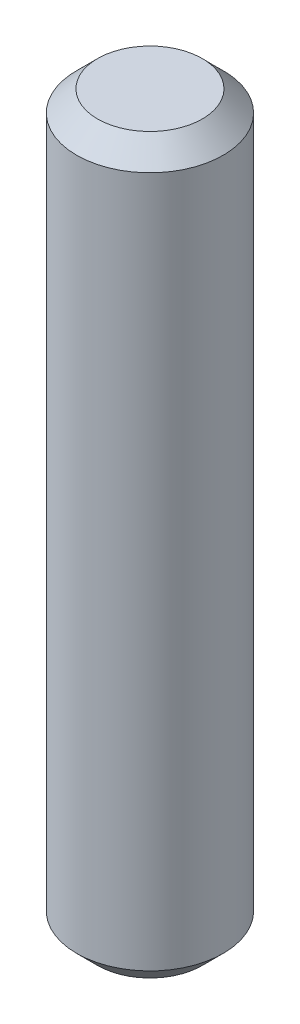
SolidWorks part; units mm, degrees
ref_plane "Front Plane" through (0, 0, 0) normal (0, 0, 1) x (1, 0, 0)
ref_plane "Top Plane" through (0, 0, 0) normal (0, 1, 0) x (1, 0, 0)
ref_plane "Right Plane" through (0, 0, 0) normal (1, 0, 0) x (0, 0, -1)
sketch "Sketch2" plane through (0, 0, 0) normal (0, 1, 0) x (1, 0, 0)
  circle A0 centre (0, 0) radius 7
  dimension "D1" = 14
extrude "Boss-Extrude1" add sketch "Sketch2" along normal mid plane 70
chamfer "Chamfer1" distance 2 angle 45 2 edges at (0, -35, 7) (0, 35, 7)
